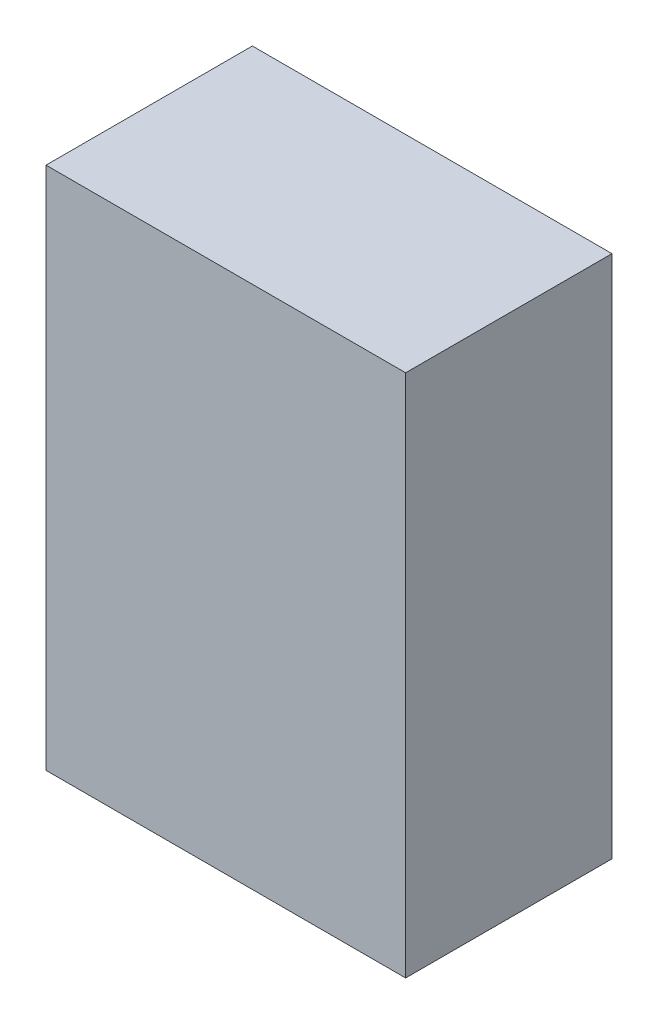
SolidWorks part; units mm, degrees
ref_plane "Front Plane" through (0, 0, 0) normal (0, 0, 1) x (1, 0, 0)
ref_plane "Top Plane" through (0, 0, 0) normal (0, 1, 0) x (1, 0, 0)
ref_plane "Right Plane" through (0, 0, 0) normal (1, 0, 0) x (0, 0, -1)
sketch "Sketch1" plane through (0, 0, 0) normal (0, 0, 1) x (1, 0, 0)
  line L1 (0, 0) -> (43.57, 0)
  line L2 (0, 0) -> (0, 63.5)
  line L3 (0, 63.5) -> (43.57, 63.5)
  line L4 (43.57, 0) -> (43.57, 63.5)
  dimension "D1" = 43.57
  dimension "D2" = 63.5
extrude "Boss-Extrude1" add sketch "Sketch1" along normal blind 25
sketch "Sketch3" plane through (43.57, 0, 0) normal (1, 0, 0) x (0, 0, -1)
  line L0 (-14.5, 0) -> (-14.5, 1.5)
  line L1 (-25, 0) -> (0, 0) construction
  line L2 (-13, 3) -> (-12, 3)
  line L3 (-10.5, 1.5) -> (-10.5, 0)
  line L4 (-10.5, 0) -> (-7.5, 0)
  line L5 (-7.5, 0) -> (-7.5, 3.5)
  line L6 (-9, 5) -> (-16, 5)
  line L7 (-17.5, 3.5) -> (-17.5, 0)
  line L8 (-17.5, 0) -> (-14.5, 0)
  line L9 (-12.5, 3) -> (-12.5, 0) construction
  arc A0 (-14.5, 1.5) -> (-13, 3) centre (-13, 1.5) cw
  arc A1 (-12, 3) -> (-10.5, 1.5) centre (-12, 1.5) cw
  arc A2 (-7.5, 3.5) -> (-9, 5) centre (-9, 3.5) ccw
  arc A3 (-16, 5) -> (-17.5, 3.5) centre (-16, 3.5) ccw
  point P14 (-14.5, 3)
  point P17 (-10.5, 3)
  dimension "D6" = 1.5
  dimension "D1" = 4
  dimension "D2" = 3
  dimension "D3" = 3
  dimension "D4" = 2
  dimension "D5" = 3
extrude "Cut-Extrude2" cut sketch "Sketch3" against normal through all
sketch "Sketch4" plane through (0, 0, 0) normal (0, -1, 0) x (1, 0, 0)
  line L0 (21.785, 25) -> (21.785, 0) construction
  line L1 (0, 25) -> (43.57, 25)
  line L2 (0, 25) -> (0, 0)
  line L3 (0, 0) -> (43.57, 0)
  line L4 (43.57, 25) -> (43.57, 0)
  line L5 (7.785, 20) -> (7.785, 5)
  line L6 (7.785, 5) -> (13.785, 5)
  line L7 (13.785, 5) -> (13.785, 20)
  line L8 (13.785, 20) -> (7.785, 20)
  line L9 (13.785, 12.5) -> (21.785, 12.5) construction
  line L10 (35.785, 5) -> (29.785, 5)
  line L11 (29.785, 5) -> (29.785, 20)
  line L12 (35.785, 20) -> (35.785, 5)
  line L13 (29.785, 20) -> (35.785, 20)
  point P12 (13.785, 20.3247)
  dimension "D1" = 6
  dimension "D2" = 8
  dimension "D3" = 15
extrude "Boss-Extrude2" add sketch "Sketch4" against normal blind 9
